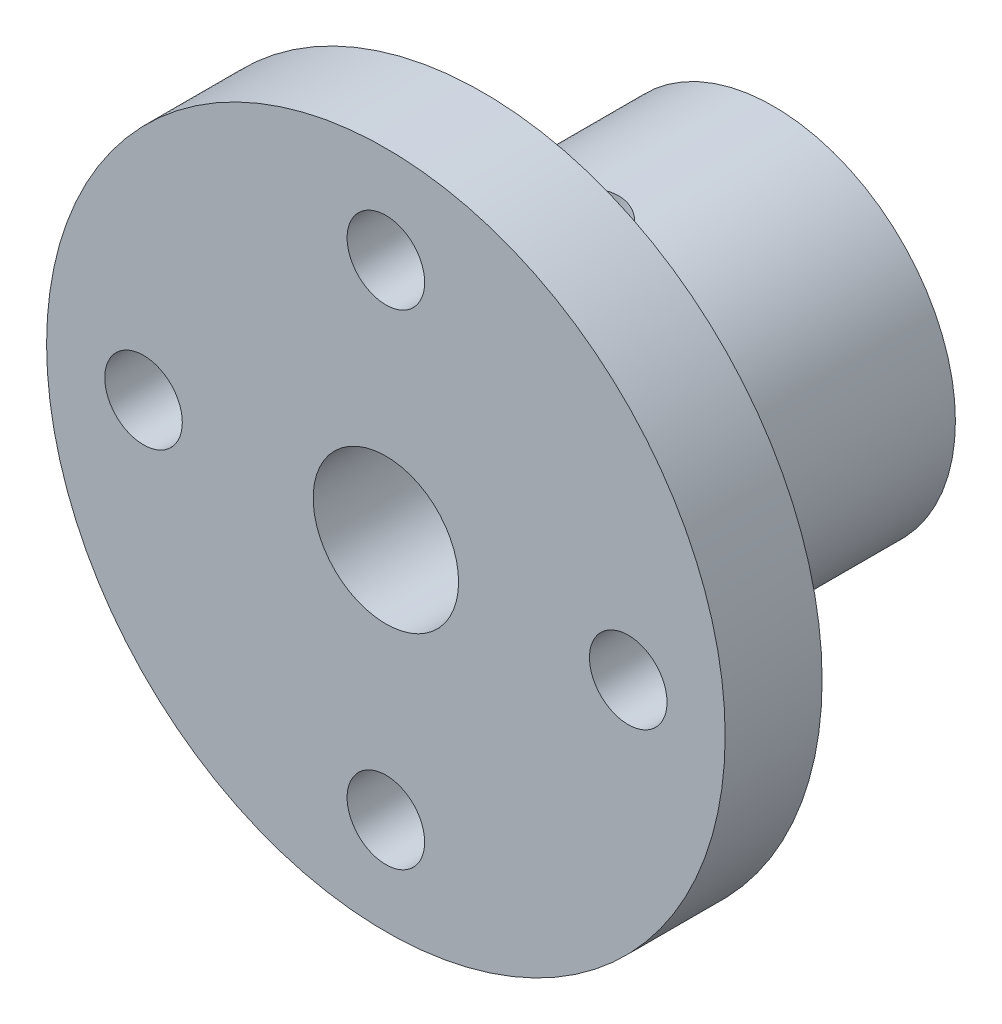
SolidWorks part; units mm, degrees
ref_plane "正面" through (0, 0, 0) normal (0, 0, 1) x (1, 0, 0)
ref_plane "平面" through (0, 0, 0) normal (0, 1, 0) x (1, 0, 0)
ref_plane "右側面" through (0, 0, 0) normal (1, 0, 0) x (0, 0, -1)
sketch "ｽｹｯﾁ1" plane through (0, 0, 0) normal (0, 0, 1) x (1, 0, 0)
  circle A0 centre (0, 0) radius 7.5
  dimension "D1" = 15
extrude "ﾎﾞｽ - 押し出し1" add sketch "ｽｹｯﾁ1" against normal blind 16
sketch "ｽｹｯﾁ2" plane through (0, 0, 0) normal (0, 0, 1) x (1, 0, 0)
  circle A0 centre (0, 0) radius 14
  dimension "D1" = 28
extrude "ﾎﾞｽ - 押し出し2" add sketch "ｽｹｯﾁ2" against normal blind 4
sketch "ｽｹｯﾁ3" plane through (0, 0, 0) normal (0, 0, 1) x (1, 0, 0)
  circle A0 centre (0, 0) radius 3
  circle A1 centre (10, 0) radius 1.6
  circle A3 centre (0, -10) radius 1.6
  circle A4 centre (-10, 0) radius 1.6
  circle A5 centre (0, 10) radius 1.6
  point P14 (0, 0)
  dimension "D1" = 6
  dimension "D2" = 3.2
  dimension "D3" = 10
  dimension "D4" = 4
extrude "ｶｯﾄ - 押し出し1" cut sketch "ｽｹｯﾁ3" against normal through all
ref_plane "平面1" through (0, 7.5, 0) normal (0, 1, 0) x (1, 0, 0)
sketch "ｽｹｯﾁ4" plane through (0, 7.5, 0) normal (0, 1, 0) x (1, 0, 0)
  line L1 (7.5, 16) -> (-7.5, 16) construction
  circle A0 centre (0, 8) radius 1.6
  dimension "D1" = 3.2
  dimension "D2" = 8
extrude "ｶｯﾄ - 押し出し2" cut sketch "ｽｹｯﾁ4" against normal blind 7.5
